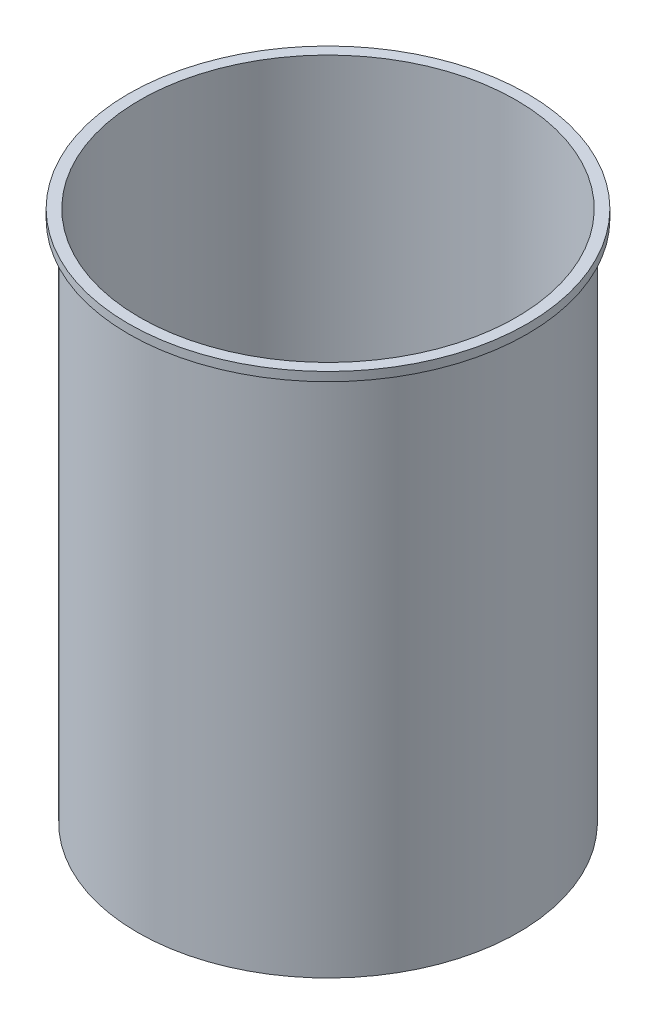
SolidWorks part; units mm, degrees
material "Brass"
ref_plane "Front Plane" through (0, 0, 0) normal (0, 0, 1) x (1, 0, 0)
ref_plane "Top Plane" through (0, 0, 0) normal (0, 1, 0) x (1, 0, 0)
ref_plane "Right Plane" through (0, 0, 0) normal (1, 0, 0) x (0, 0, -1)
sketch "Sketch1" plane through (0, 0, 0) normal (0, 1, 0) x (1, 0, 0)
  circle A0 centre (0, 0) radius 42.5
  circle A1 centre (0, 0) radius 43
  dimension "D1" = 85
  dimension "D2" = 0.5
extrude "Boss-Extrude1" add sketch "Sketch1" along normal blind 118
sketch "Sketch2" plane through (0, 118, 0) normal (0, 1, 0) x (1, 0, 0)
  circle A0 centre (0, 0) radius 45
  circle A1 centre (0, 0) radius 42.5 construction
  circle A2 centre (0, 0) radius 42.5
  dimension "D1" = 90
extrude "Boss-Extrude2" add sketch "Sketch2" along normal blind 2
